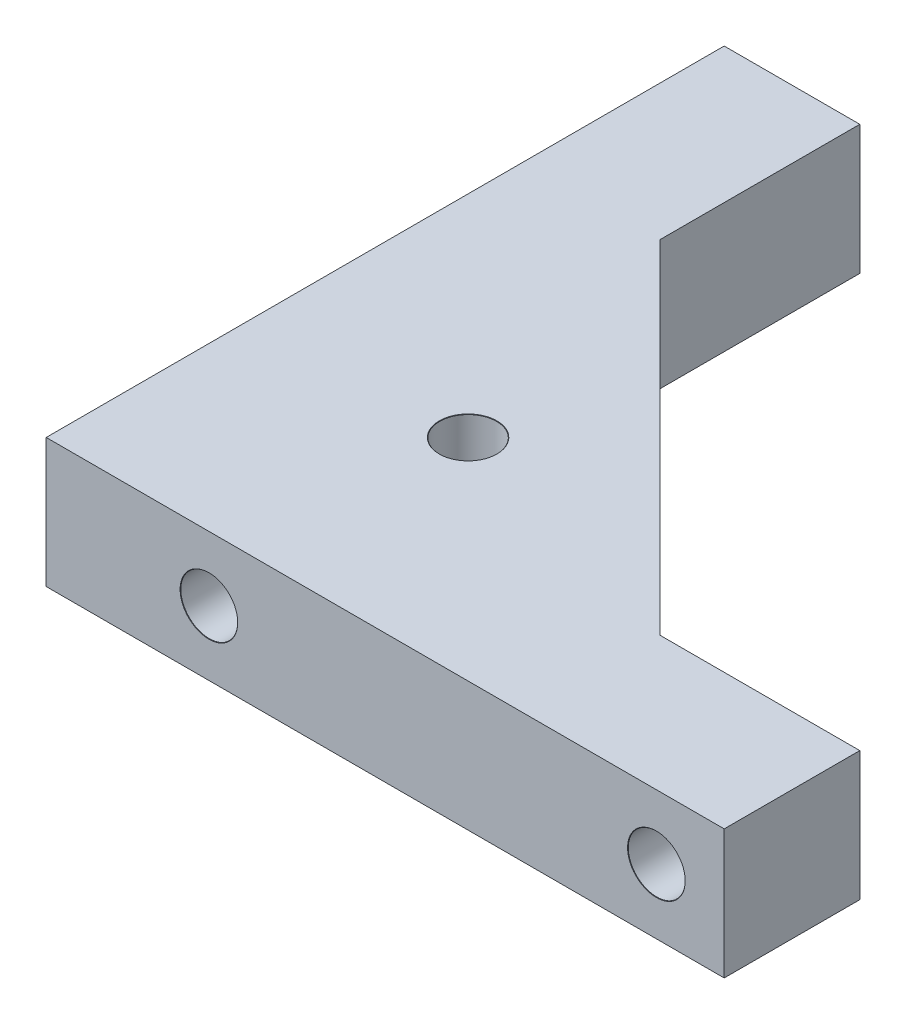
SolidWorks part; units mm, degrees
material "AISI 1045 Steel, cold drawn"
ref_plane "Front Plane" through (0, 0, 0) normal (0, 0, 1) x (1, 0, 0)
ref_plane "Top Plane" through (0, 0, 0) normal (0, 1, 0) x (1, 0, 0)
ref_plane "Right Plane" through (0, 0, 0) normal (1, 0, 0) x (0, 0, -1)
sketch "Sketch1" plane through (0, 0, 0) normal (0, 1, 0) x (1, 0, 0)
  line L0 (0, 0) -> (50, 0)
  line L1 (50, 0) -> (50, 10)
  line L2 (50, 10) -> (35.2548, 10)
  line L3 (35.2548, 10) -> (10, 35.2548)
  line L4 (10, 35.2548) -> (10, 50)
  line L5 (10, 50) -> (0, 50)
  line L6 (0, 50) -> (0, 0)
  dimension "D1" = 10
  dimension "D2" = 50
  dimension "D3" = 32
extrude "Boss-Extrude1" add sketch "Sketch1" along normal mid plane 9.525
hole_wizard "Tap Drill for M5x0.8 Tap1" positions "Sketch4" profile "Sketch6" hole size "M5x0.8" standard "ANSI Metric"
sketch "Sketch4" plane through (0, 0, 0) normal (0, 0, 1) x (1, 0, 0)
  line L0 (12, 0) -> (45, 0) construction
  line L2 (50, 4.7625) -> (50, -4.7625) construction
  line L3 (0, 4.7625) -> (0, -4.7625) construction
  point P0 (12, 0)
  point P2 (45, 0)
  point P13 (50, 0)
  dimension "D1" = 5
  dimension "D2" = 12
sketch "Sketch6" plane through (12, 0, 0) normal (1, 0, 0) x (0, -1, 0)
  line L0 (0, 0) -> (0, 9.2618)
  line L1 (0, 9.2618) -> (2.1, 8)
  line L2 (2.1, 8) -> (2.1, 0.025)
  line L3 (2.1, 0.025) -> (2.125, 0)
  line L5 (2.125, 0) -> (0, 0)
  line L6 (-2.1, 0.025) -> (-2.125, 0) construction
  line L10 (0, 9.2618) -> (-2.1, 8) construction
  line L11 (0, -6.35) -> (0, 107.95) construction
  dimension "Hole Dia." = 4.2
  dimension "Hole Depth" = 8
  dimension "Near C'Sink Dia." = 4.25
  dimension "Near C'Sink Angle" = 90
  dimension "Drill Angle" = 118
ref_plane "Plane1" through (0, 0, 0) normal (0.7071, 0, 0.7071) x (0.7071, 0, -0.7071)
mirror "Mirror1" about plane through (0, 0, 0) normal (0.7071, 0, 0.7071) of "Tap Drill for M5x0.8 Tap1"
hole_wizard "Tap Drill for M5x0.8 Tap2" positions "Sketch8" profile "Sketch10" hole size "M5x0.8" standard "ANSI Metric" end condition through all
sketch "Sketch8" plane through (0, 4.7625, 0) normal (0, 1, 0) x (1, 0, 0)
  line L0 (22.6274, 22.6274) -> (0, 0) construction
  line L1 (35.2548, 10) -> (10, 35.2548) construction
  point P0 (15.5563, 15.5563)
  point P10 (15.1847, 15.1847)
  dimension "D1" = 10
sketch "Sketch10" plane through (15.5563, 4.7625, -15.5563) normal (1, 0, 0) x (0, 0, 1)
  line L0 (0, 0) -> (0, 9.525)
  line L1 (0, 9.525) -> (2.125, 9.525)
  line L2 (2.1, 9.5) -> (2.1, 0.025)
  line L3 (2.1, 0.025) -> (2.125, 0)
  line L5 (2.125, 0) -> (0, 0)
  line L6 (-2.1, 0.025) -> (-2.125, 0) construction
  line L7 (2.125, 9.525) -> (2.1, 9.5)
  line L8 (-2.125, 9.525) -> (-2.1, 9.5) construction
  line L11 (0, -6.35) -> (0, 107.95) construction
  dimension "Thru Hole Dia." = 4.2
  dimension "Thru Hole Depth" = 9.525
  dimension "Near C'Sink Dia." = 4.25
  dimension "Near C'Sink Angle" = 90
  dimension "Far C'Sink Dia." = 4.25
  dimension "Far C'Sink Angle" = 90
